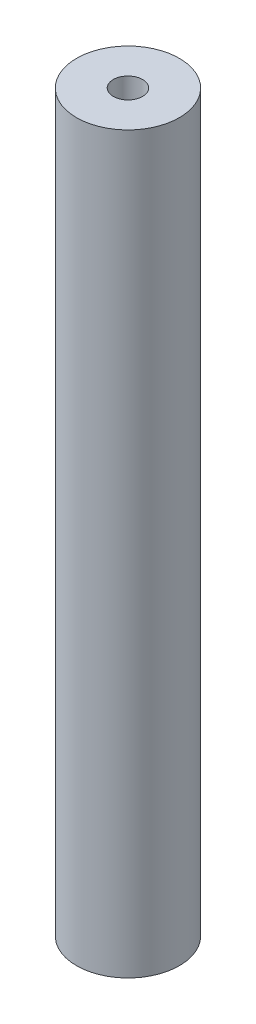
SolidWorks part; units mm, degrees
ref_plane "Front Plane" through (0, 0, 0) normal (0, 0, 1) x (1, 0, 0)
ref_plane "Top Plane" through (0, 0, 0) normal (0, 1, 0) x (1, 0, 0)
ref_plane "Right Plane" through (0, 0, 0) normal (1, 0, 0) x (0, 0, -1)
sketch "Sketch1" plane through (0, 0, 0) normal (0, 1, 0) x (1, 0, 0)
  circle A0 centre (0, 0) radius 8.75
extrude "Boss-Extrude1" add sketch "Sketch1" along normal blind 125
sketch "Sketch2" plane through (0, 0, 0) normal (0, 1, 0) x (1, 0, 0)
  circle A0 centre (0, 0) radius 2.5
extrude "Cut-Extrude1" cut sketch "Sketch2" along normal blind 131
